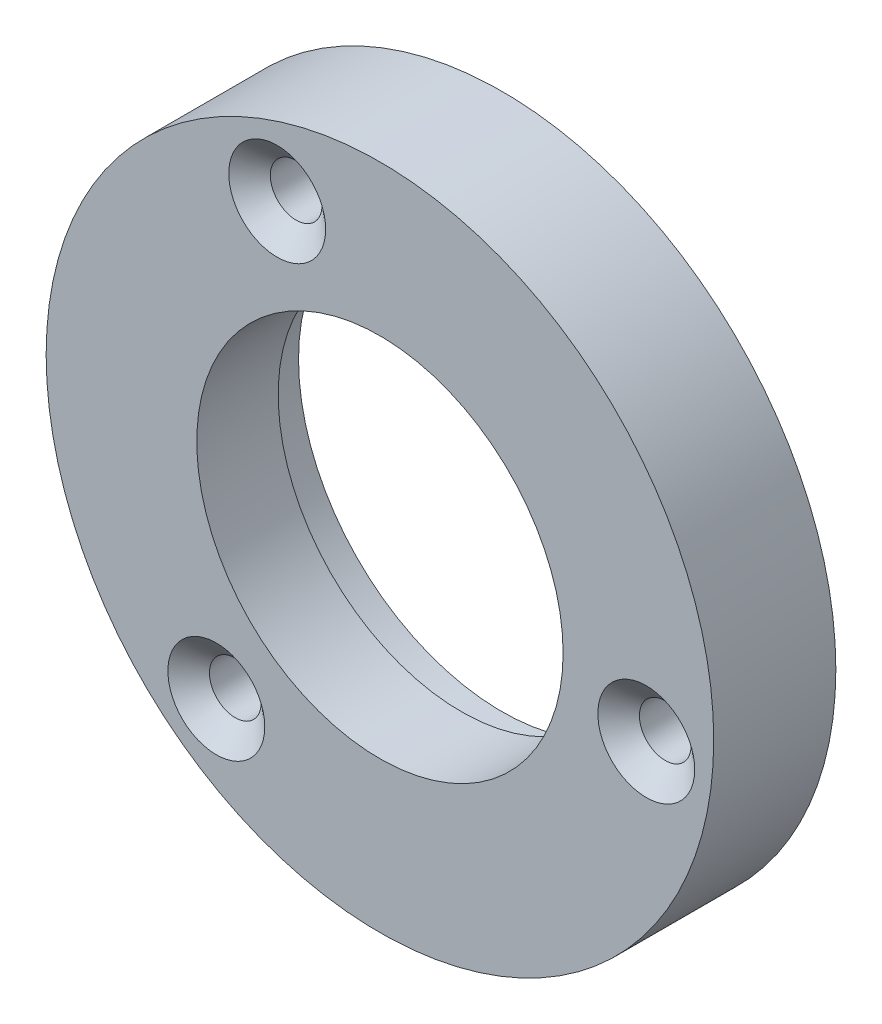
SolidWorks part; units mm, degrees
material "Copper"
ref_plane "Front Plane" through (0, 0, 0) normal (0, 0, 1) x (1, 0, 0)
ref_plane "Top Plane" through (0, 0, 0) normal (0, 1, 0) x (1, 0, 0)
ref_plane "Right Plane" through (0, 0, 0) normal (1, 0, 0) x (0, 0, -1)
sketch "Sketch1" plane through (0, 0, 0) normal (0, 0, 1) x (1, 0, 0)
  circle A0 centre (0, 0) radius 10.414
  dimension "D1" = 20.828
extrude "Boss-Extrude1" add sketch "Sketch1" along normal blind 3.81
sketch "Sketch2" plane through (0, 0, 3.81) normal (0, 0, 1) x (1, 0, 0)
  circle A0 centre (0, 0) radius 5.715
  dimension "D1" = 11.43
extrude "Cut-Extrude1" cut sketch "Sketch2" against normal through all
sketch "Sketch3" plane through (0, 0, 0) normal (0, 0, -1) x (-1, 0, 0)
  circle A0 centre (0, 0) radius 6.35
  dimension "D1" = 12.7
extrude "Cut-Extrude3" cut sketch "Sketch3" against normal blind 1.27 contours A0
sketch "Sketch9" plane through (0, 0, 3.81) normal (0, 0, 1) x (1, 0, 0)
  line L0 (0, -10.414) -> (0, -5.715)
  circle A0 centre (0, 0) radius 10.414 construction
  circle A1 centre (0, 0) radius 5.715 construction
  point P7 (0, -8.0645)
sketch "Sketch10" plane through (0, 0, 3.81) normal (0, 0, 1) x (1, 0, 0)
  line L0 (0, 0) -> (7.6048, 8.533)
  dimension "D1" = 11.43
ref_point "Point1"
sketch "Sketch13" plane through (0, 0, 3.81) normal (0, 0, 1) x (1, 0, 0)
  line L0 (0, 0) -> (-5.1046, -6.6483)
  dimension "D1" = 8.382
hole_wizard "CSK for #0 Flat Head Machine Screw (100)1" positions "Sketch25" profile "Sketch26" countersink size "#0" standard "ANSI Inch" end condition through all
sketch "Sketch25" plane through (0, 0, 3.81) normal (0, 0, 1) x (1, 0, 0)
  point P0 (-5.1046, -6.6483)
sketch "Sketch26" plane through (-5.1046, -6.6483, 3.81) normal (1, 0, 0) x (0, -1, 0)
  line L0 (0, 0) -> (0, 3.81)
  line L1 (0, 3.81) -> (0.8064, 3.81)
  line L2 (0.8064, 3.81) -> (0.8064, 0.5914)
  line L3 (0.8064, 0.5914) -> (1.5113, 0)
  line L5 (1.5113, 0) -> (0, 0)
  line L6 (-0.8064, 0.5914) -> (-1.5113, 0) construction
  line L11 (0, -6.35) -> (0, 107.95) construction
  dimension "Thru Hole Dia." = 1.6129
  dimension "Thru Hole Depth" = 3.81
  dimension "Near C'Sink Dia." = 3.0226
  dimension "Near C'Sink Angle" = 100
pattern_circular "CirPattern1" count 3 every 120 about axis through (0, 0, 0) along (0, 0, 1) of "CSK for #0 Flat Head Machine Screw (100)1"
